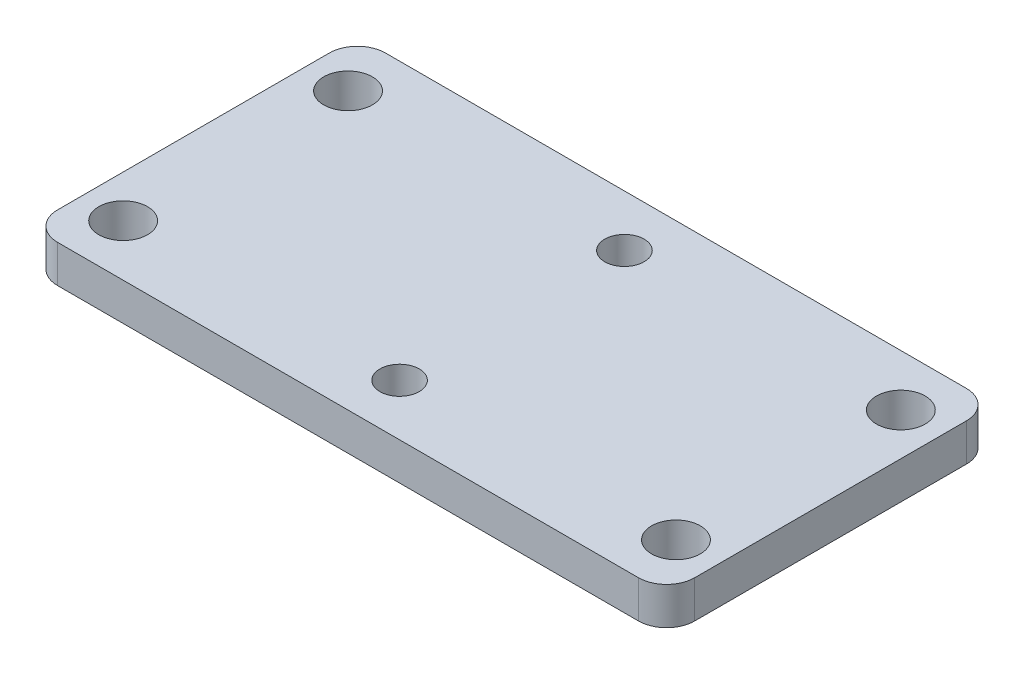
SolidWorks part; units mm, degrees
ref_plane "前视基准面" through (0, 0, 0) normal (0, 0, 1) x (1, 0, 0)
ref_plane "上视基准面" through (0, 0, 0) normal (0, 1, 0) x (1, 0, 0)
ref_plane "右视基准面" through (0, 0, 0) normal (1, 0, 0) x (0, 0, -1)
other "Configuration Table"
sketch "草图1" plane through (0, 0, 0) normal (0, 1, 0) x (1, 0, 0)
  line L1 (-34, -17.5) -> (34, -17.5)
  line L2 (-34, -17.5) -> (-34, 17.5)
  line L3 (-34, 17.5) -> (34, 17.5)
  line L4 (34, -17.5) -> (34, 17.5)
  line L5 (-34, -17.5) -> (34, 17.5) construction
  line L6 (-34, 17.5) -> (34, -17.5) construction
  point P0 (0, 0)
  dimension "D1" = 68
  dimension "D2" = 35
extrude "凸台-拉伸1" add sketch "草图1" along normal blind 4
sketch "草图2" plane through (0, 4, 0) normal (0, 1, 0) x (1, 0, 0)
  line L0 (0, 0) -> (0, 7.473) construction
  line L1 (0, 0) -> (-16.9276, 0) construction
  circle A0 centre (-29.5, 12) radius 2.6
  circle A1 centre (29.5, 12) radius 2.6
  circle A2 centre (29.5, -12) radius 2.6
  circle A3 centre (-29.5, -12) radius 2.6
  circle A4 centre (0, 12) radius 2.1
  circle A5 centre (0, -12) radius 2.1
  dimension "D1" = 59
  dimension "D2" = 5.2
  dimension "D3" = 24
  dimension "D4" = 4.2
  dimension "D5" = 24
extrude "切除-拉伸1" cut sketch "草图2" against normal blind 4
fillet "圆角1" radius 3 4 edges at (34, 2, 17.5) (34, 2, -17.5) (-34, 2, 17.5) (-34, 2, -17.5)
